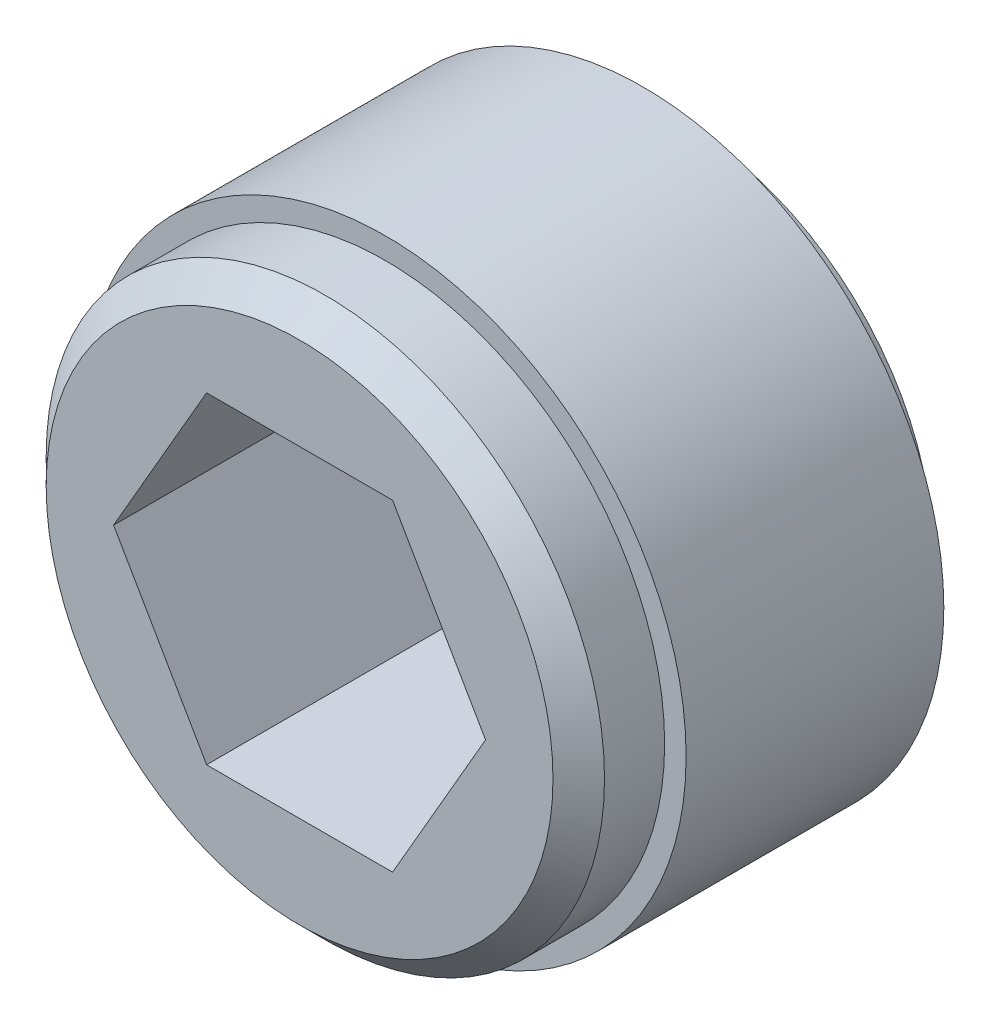
SolidWorks part; units mm, degrees
ref_plane "Front" through (0, 0, 0) normal (0, 0, 1) x (1, 0, 0)
ref_plane "Top" through (0, 0, 0) normal (0, 1, 0) x (1, 0, 0)
ref_plane "Right" through (0, 0, 0) normal (1, 0, 0) x (0, 0, -1)
sketch "Sketch1" plane through (0, 0, 0) normal (0, 0, 1) x (1, 0, 0)
  circle A0 centre (0, 0) radius 4.445
  dimension "D1" = 8.89
extrude "Boss-Extrude1" add sketch "Sketch1" along normal blind 5.08
cosmetic thread "Cosmetic Thread1" parameters "D2"=6.6777
sketch "Sketch2" plane through (0, 0, 0) normal (0, 0, -1) x (-1, 0, 0)
  circle A0 centre (0, 0) radius 3.81
  dimension "D1" = 7.62
extrude "Boss-Extrude2" add sketch "Sketch2" along normal blind 0.635 draft 15
sketch "Sketch3" plane through (0, 0, 5.08) normal (0, 0, 1) x (1, 0, 0)
  circle A0 centre (0, 0) radius 4.1275
  circle A1 centre (0, 0) radius 4.445 construction
  circle A2 centre (0, 0) radius 4.445
  circle M2 centre (0, 0) radius 4.445
  dimension "D1" = 8.255
extrude "Cut-Extrude1" cut sketch "Sketch3" against normal blind 1.27 contours A0 M2 | A2
chamfer "Chamfer1" distance 0.381 1 edges at (4.1275, 0, 5.08)
sketch "Sketch5" plane through (0, 0, 5.08) normal (0, 0, 1) x (1, 0, 0)
  line L1 (-1.3748, 2.3813) -> (-2.7496, 0)
  line L2 (-2.7496, 0) -> (-1.3748, -2.3813)
  line L3 (-1.3748, -2.3813) -> (1.3748, -2.3813)
  line L4 (1.3748, -2.3813) -> (2.7496, 0)
  line L5 (2.7496, 0) -> (1.3748, 2.3813)
  line L6 (1.3748, 2.3813) -> (-1.3748, 2.3813)
  circle A0 centre (0, 0) radius 2.3813 construction
  dimension "D1" = 4.7625
extrude "Cut-Extrude2" cut sketch "Sketch5" against normal through all
